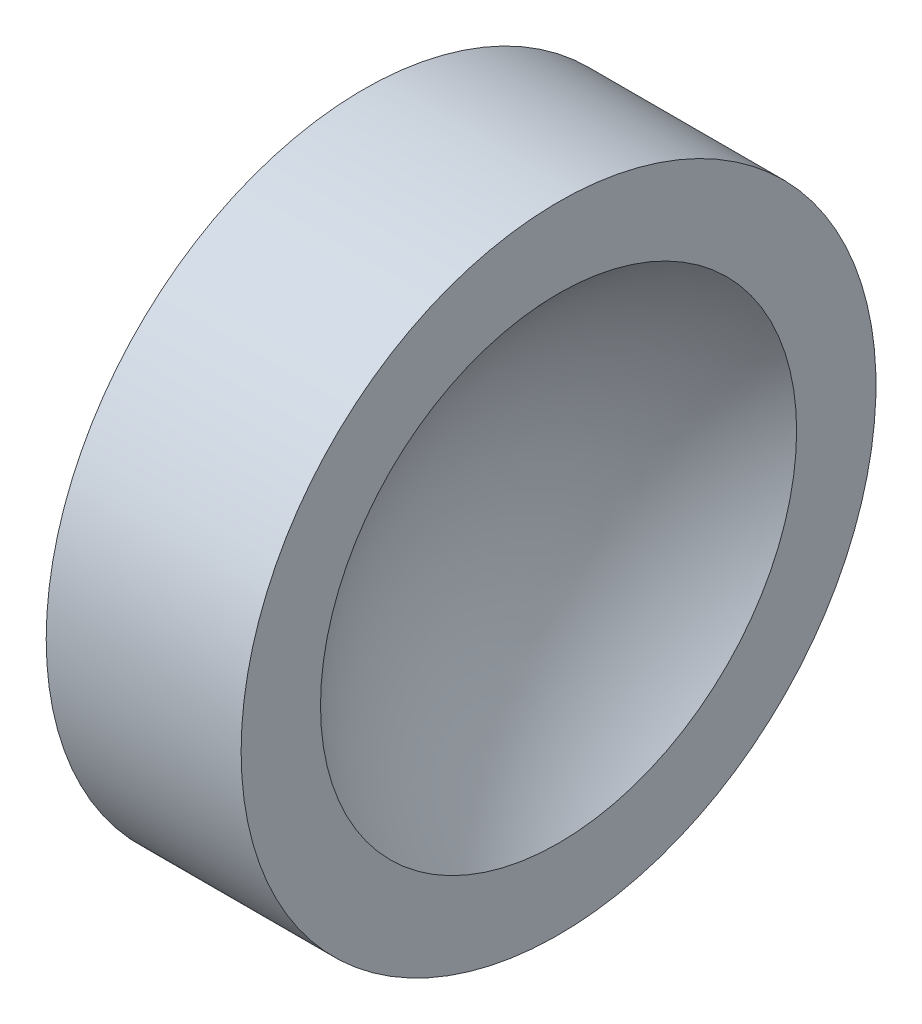
SolidWorks part; units mm, degrees
ref_plane "前视基准面" through (0, 0, 0) normal (0, 0, 1) x (1, 0, 0)
ref_plane "上视基准面" through (0, 0, 0) normal (0, 1, 0) x (1, 0, 0)
ref_plane "右视基准面" through (0, 0, 0) normal (1, 0, 0) x (0, 0, -1)
sketch "草图1" plane through (0, 0, 0) normal (0, 0, 1) x (1, 0, 0)
  line L0 (0, -2.0339) -> (0, 2.0339)
  line L1 (0, 2.0339) -> (1.2489, 2.0339)
  line L2 (1.2489, 2.0339) -> (1.2489, 1.5253)
  line L3 (0, 0) -> (1.1922, 0) construction
  line L4 (1.2489, -2.0339) -> (1.2489, -1.5253)
  line L5 (0, -2.0339) -> (1.2489, -2.0339)
  arc A0 (1.2489, 1.5253) -> (1.2489, -1.5253) centre (2.7986, 0) ccw
  point P9 (1.2724, 1.175)
  point P10 (0, 0)
  point P11 (1.2489, 1.2621)
  dimension "D2" = 2.7986
  dimension "D1" = 2.0339
  dimension "D3" = 1.5253
revolve "旋转2" add sketch "草图1" angle 360 about L3
